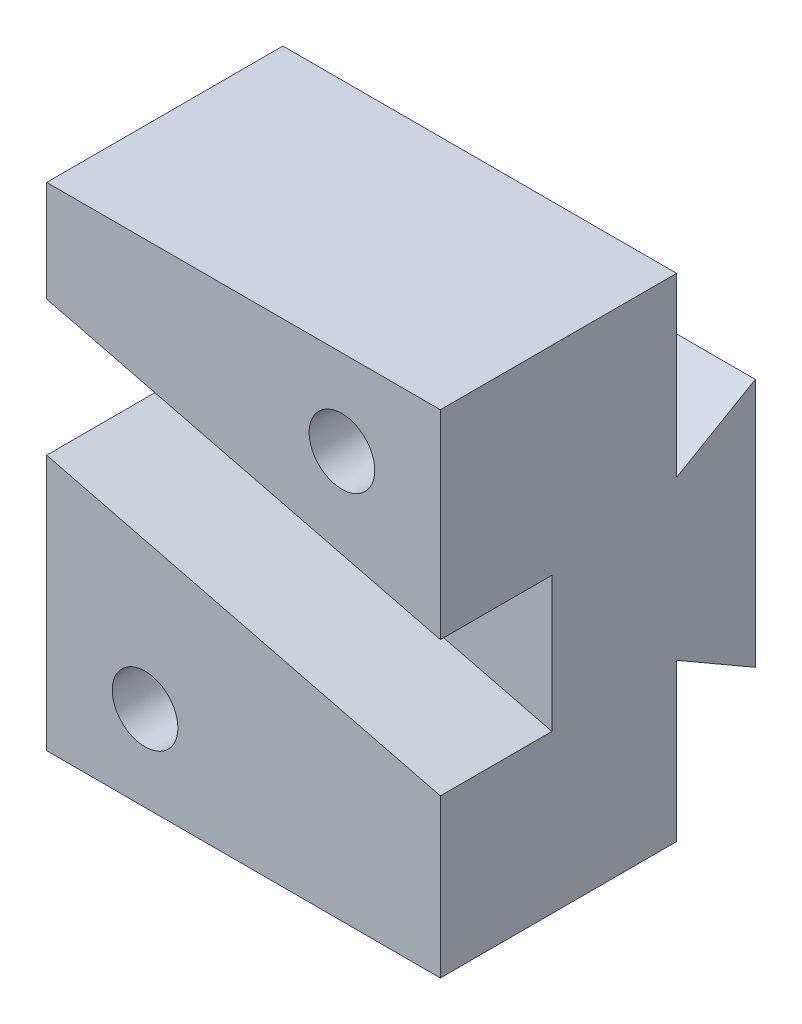
SolidWorks part; units mm, degrees
ref_plane "Front Plane" through (0, 0, 0) normal (0, 0, 1) x (1, 0, 0)
ref_plane "Top Plane" through (0, 0, 0) normal (0, 1, 0) x (1, 0, 0)
ref_plane "Right Plane" through (0, 0, 0) normal (1, 0, 0) x (0, 0, -1)
sketch "Sketch1" plane through (0, 0, 0) normal (1, 0, 0) x (0, 0, -1)
  line L0 (-36, 75) -> (0, 75)
  line L1 (0, 75) -> (0, 48.0718)
  line L2 (0, 48.0718) -> (12, 55)
  line L3 (12, 55) -> (12, 17)
  line L4 (12, 17) -> (0, 23.9282)
  line L5 (0, 23.9282) -> (0, 0)
  line L6 (0, 0) -> (-36, 0)
  line L7 (-36, 0) -> (-36, 75)
  point P8 (0, 0)
  dimension "D1" = 36
  dimension "D2" = 48
  dimension "D3" = 60
  dimension "D4" = 60
  dimension "D5" = 38
  dimension "D6" = 17
  dimension "D7" = 75
extrude "Boss-Extrude1" add sketch "Sketch1" along normal blind 60
sketch "Sketch2" plane through (0, 0, 36) normal (0, 0, 1) x (1, 0, 0)
  line L0 (0, 59.6123) -> (60, 44.6526)
  line L2 (0, 39) -> (60, 24.0403)
  line L5 (0, 75) -> (0, 0) construction
  line L6 (60, 75) -> (60, 0) construction
  line L7 (0, 59.6123) -> (0, 39)
  line L8 (60, 44.6526) -> (60, 24.0403)
  line L9 (60, 0) -> (0, 0) construction
  line L10 (60, 75) -> (0, 75) construction
  circle A0 centre (45, 62) radius 5
  circle A1 centre (15, 13) radius 5
  point P13 (13.6892, 12.3249)
  dimension "D4" = 10
  dimension "D1" = 20
  dimension "D2" = 39
  dimension "D3" = 76
  dimension "D5" = 15
  dimension "D6" = 13
  dimension "D7" = 13
  dimension "D8" = 15
extrude "Cut-Extrude1" cut sketch "Sketch2" against normal blind 17 contours L8 L2 L7 L0
sketch "Sketch4" plane through (0, 0, 36) normal (0, 0, 1) x (1, 0, 0)
  line L0 (60, 75) -> (0, 75) construction
  line L1 (60, 75) -> (60, 44.6526) construction
  line L2 (60, 0) -> (0, 0) construction
  line L3 (0, 39) -> (0, 0) construction
  circle A0 centre (45, 62) radius 5
  circle A1 centre (15, 13) radius 5
  point P8 (11.7728, 12.5591)
  dimension "D1" = 13
  dimension "D2" = 15
  dimension "D3" = 10
  dimension "D4" = 13
  dimension "D5" = 15
extrude "Cut-Extrude2" cut sketch "Sketch4" against normal up to next
